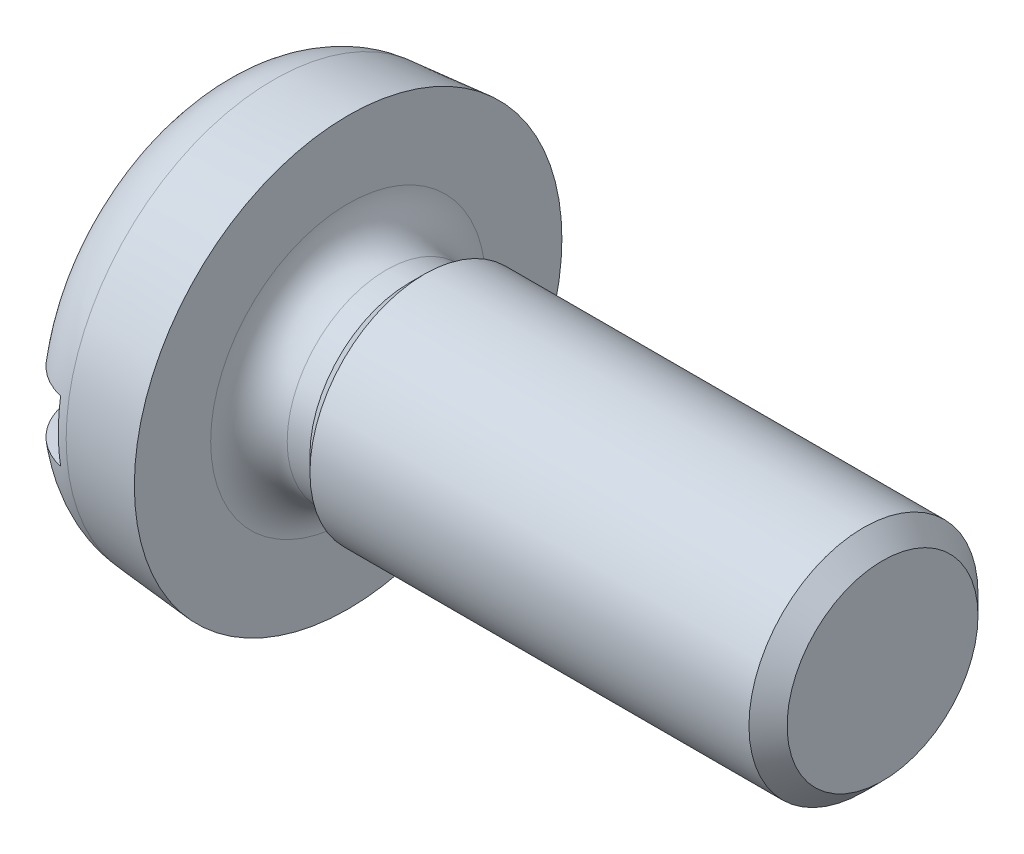
SolidWorks part; units mm, degrees
revolve "基体-旋转" add sketch "草图3" angle 360 about L0
sketch "草图3" plane through (0, 0, 0) normal (0, 0, 1) x (1, 0, 0)
  line L0 (-2.477, 0) -> (6.7868, 0) construction
  line L1 (0, 0) -> (13.8, 0)
  line L2 (13.8, 0) -> (13.8, 1.5)
  line L3 (13.8, 1.5) -> (2.8, 1.5)
  line L4 (1.8, 1.8) -> (1.8, 2.8)
  line L5 (2.8, 1.5) -> (2.599, 1.299)
  line L6 (2.599, 1.299) -> (2.301, 1.299)
  line L7 (1.8, 2.8) -> (0.8216, 2.7144)
  line L9 (0, 1.8178) -> (0, 0)
  arc A0 (2.301, 1.299) -> (1.8, 1.8) centre (2.301, 1.8) cw
  arc A1 (0.8216, 2.7144) -> (0, 1.8178) centre (0.9, 1.8178) ccw
  dimension "D5" = 0.9
  dimension "dk" = 5.6
  dimension "d" = 3
  dimension "D2" = 5
  dimension "l" = 12
  dimension "D1" = 45
  dimension "D3" = 2.598
  dimension "D4" = 11
  dimension "da" = 3.6
  dimension "k" = 1.8
cosmetic thread "装饰螺纹线1" parameters "D1"=11, "D2"=2.598
material "4.8级"
ref_plane "前视" through (0, 0, 0) normal (0, 0, 1) x (1, 0, 0)
ref_plane "上视" through (0, 0, 0) normal (0, 1, 0) x (1, 0, 0)
ref_plane "右视" through (0, 0, 0) normal (1, 0, 0) x (0, 0, -1)
sketch "尺寸草图" plane through (0, 0, 0) normal (0, 0, 1) x (1, 0, 0)
  line L0 (0, 0) -> (12, 0)
  line L1 (0, 0) -> (0, 5.6)
  line L2 (12, 0) -> (12, 3.6)
  point P5 (11.5, 0)
  point P6 (1.8, 0)
  point P7 (0.8, 0)
  point P8 (1, 0)
  point P9 (12, 0.1)
  point P10 (11.1, 0)
  point P11 (0, 0.7)
  point P12 (12, 3)
  dimension "dk" = 5.6
  dimension "d" = 3
  dimension "l" = 12
  dimension "da" = 3.6
  dimension "k" = 1.8
  dimension "P" = 0.5
  dimension "a" = 1
  dimension "n" = 0.8
  dimension "r" = 0.1
  dimension "rf" = 0.9
  dimension "t" = 0.7
sketch "草图4" plane through (0, 0, 0) normal (0, 0, 1) x (1, 0, 0)
  line L0 (0, 1.8178) -> (0, -1.8178) construction
  line L1 (0, 0.4) -> (0.7, 0.4)
  line L2 (0, 0.4) -> (0, -0.4)
  line L3 (0, -0.4) -> (0.7, -0.4)
  line L4 (0.7, 0.4) -> (0.7, -0.4)
  point P6 (0, 0)
  dimension "n" = 0.8
  dimension "t" = 0.7
extrude "切除-拉伸1" cut sketch "草图4" against normal mid plane 100
sketch "草图5" plane through (0, 0, 0) normal (0, 0, 1) x (1, 0, 0)
  line L0 (13.5473, 1.5) -> (14.0473, 1.5)
  line L1 (14.0473, 1.5) -> (13.8, 1.067)
  line L2 (13.8, 1.067) -> (13.5473, 1.5)
  line L3 (13.8, 1.5) -> (2.8, 1.5) construction
  line L4 (13.8, -1.5) -> (13.8, 1.5) construction
  line L5 (6.175, 0) -> (-0.2582, 0) construction
  line L6 (-2.477, 0) -> (6.7868, 0) construction
  dimension "P" = 0.5
  dimension "D1" = 0.433
  dimension "D2" = 60
revolve "切除-旋转1" cut sketch "草图5" angle 360 about L5
pattern_linear "阵列(线性)1" [suppressed] count 23 spacing 0.5 along (1, 0, 0)
sketch "草图6" plane through (13.8, 0, 0) normal (1, 0, 0) x (0, 0, -1)
  circle A0 centre (0, 0) radius 4.9639
extrude "切除-拉伸2" cut sketch "草图6" against normal blind 5
chamfer "倒角1" distance 0.25 angle 45 1 edges at (8.8, 0, -1.5)
equation "\"l@草图3\" = \"l@尺寸草图\""
equation "\"dk@草图3\"=\"dk@尺寸草图\""
equation "\"da@草图3\" = \"da@尺寸草图\""
equation "\"D3@草图3\" = \"d@尺寸草图\"*0.866"
equation "\"D4@草图3\" = \"l@尺寸草图\"-\"a@尺寸草图\""
equation "\"d@草图3\" = \"d@尺寸草图\""
equation "\"D2@装饰螺纹线1\" = \"d@尺寸草图\"*0.866"
equation "\"D1@装饰螺纹线1\" = \"l@尺寸草图\"-\"a@尺寸草图\""
equation "\"n@草图4\" = \"n@尺寸草图\""
equation "\"t@草图4\" = \"t@尺寸草图\""
equation "\"P@草图5\" = \"P@尺寸草图\""
equation "\"D1@草图5\" = \"P@草图5\"*0.866"
equation "\"D3@阵列(线性)1\" = \"P@尺寸草图\""
equation "\"D1@阵列(线性)1\" = (\"l@尺寸草图\"-\"a@尺寸草图\")/\"P@尺寸草图\"+1"
equation "\"k@草图3\"=\"k@尺寸草图\""
equation "\"D5@草图3\"=\"rf@尺寸草图\""
